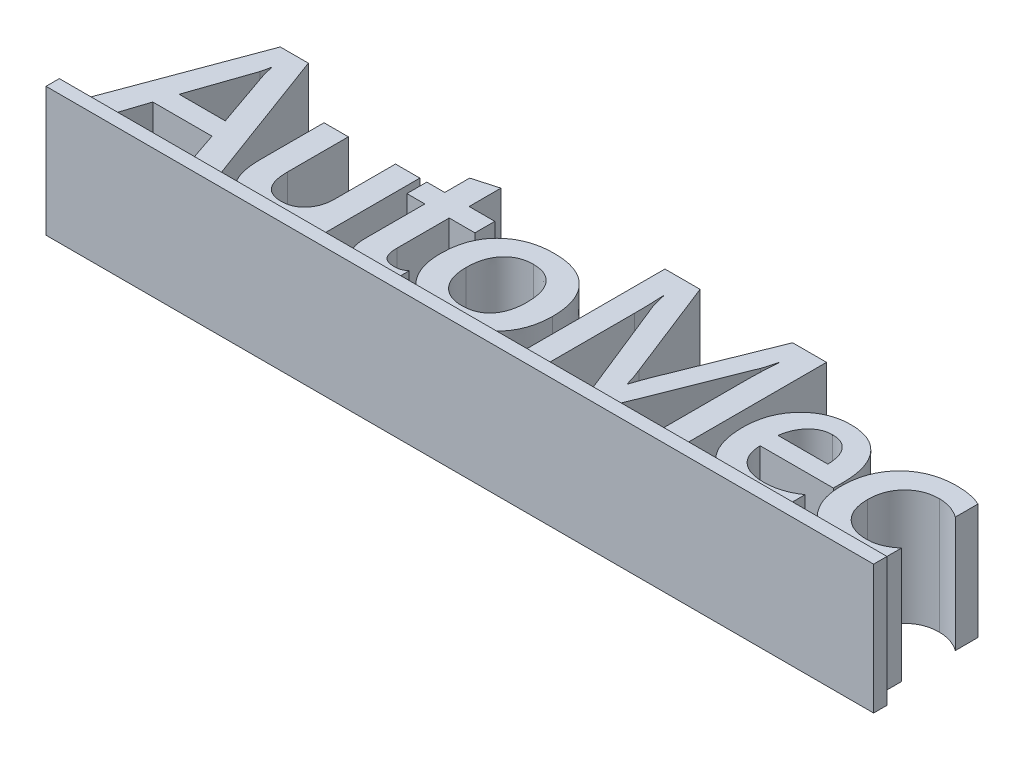
SolidWorks part; units mm, degrees
ref_plane "Front Plane" through (0, 0, 0) normal (0, 0, 1) x (1, 0, 0)
ref_plane "Top Plane" through (0, 0, 0) normal (0, 1, 0) x (1, 0, 0)
ref_plane "Right Plane" through (0, 0, 0) normal (1, 0, 0) x (0, 0, -1)
sketch "Sketch3" plane through (0, 0, 0) normal (0, 1, 0) x (1, 0, 0)
  text T0 "AutoMec" font "@Yu Gothic UI" height 34
  point P1 (0, 0)
  point P2 (0, 0)
  point P3 (0, 0)
  dimension "D1" = 2
extrude "Boss-Extrude3" add sketch "Sketch3" along normal blind 26
sketch "Sketch8" plane through (0, 0, 0) normal (0, 1, 0) x (1, 0, 0)
  line L0 (182.4796, 6.2632) -> (182.4796, 1.3002) construction
  line L1 (-0.6016, 0) -> (185.4796, 0)
  line L2 (-0.6016, 0) -> (-0.6016, -3)
  line L3 (-0.6016, -3) -> (185.4796, -3)
  line L4 (185.4796, 0) -> (185.4796, -3)
  line L5 (8.5358, 0) -> (2.3984, 0) construction
  point P8 (0, 0)
  dimension "D1" = 3
  dimension "D2" = 3
  dimension "D3" = 3
extrude "Boss-Extrude6" add sketch "Sketch8" along normal blind 29
sketch "Sketch9" plane through (0, 0, 0) normal (0, 1, 0) x (1, 0, 0)
  line L0 (185.4796, 0) -> (-0.6016, 0) construction
  line L1 (50.8205, 4.0752) -> (46.2162, 4.0752)
  line L2 (50.8205, 4.0752) -> (50.8205, 0)
  line L3 (50.8205, 0) -> (46.2162, 0)
  line L4 (46.2162, 4.0752) -> (46.2162, 0)
  spline S0 degree 3 poles (50.7226, 4.0752) (50.5199, 3.7151) (50.1266, 3.0161) (49.3956, 2.0918) (48.5875, 1.308) (47.6958, 0.6594) (46.8879, 0.2502) (46.3829, 0.0573) (46.2162, 0) knots 0 0 0 0 0.134966 0.261921 0.383686 0.502095 0.621005 0.678615 0.678615 0.678615 0.678615 construction
extrude "Boss-Extrude7" add sketch "Sketch9" along normal up to surface (26 mm away) up to face at (85.7722, 26, -12.0388)
sketch "Sketch10" plane through (0, 0, 0) normal (0, 1, 0) x (1, 0, 0)
  line L1 (73.1484, 0.3914) -> (72.2012, 0.3914)
  line L2 (73.1484, 0.3914) -> (73.1484, 0)
  line L3 (73.1484, 0) -> (72.2012, 0)
  line L4 (72.2012, 0.3914) -> (72.2012, 0)
extrude "Boss-Extrude8" add sketch "Sketch10" along normal up to surface (26 mm away) up to face at (66.6817, 26, -15.2052)
sketch "Sketch11" plane through (0, 0, 0) normal (0, 1, 0) x (1, 0, 0)
  line L1 (161.2492, 1.5588) -> (157.1624, 1.5588)
  line L2 (161.2492, 1.5588) -> (161.2492, 0)
  line L3 (161.2492, 0) -> (157.1624, 0)
  line L4 (157.1624, 1.5588) -> (157.1624, 0)
extrude "Boss-Extrude9" add sketch "Sketch11" along normal up to surface (26 mm away) up to face at (154.266, 26, -16.4035)
sketch "Sketch12" plane through (0, 0, 0) normal (0, 1, 0) x (1, 0, 0)
  line L1 (182.4796, 1.3002) -> (179.3332, 1.3002)
  line L2 (182.4796, 1.3002) -> (182.4796, 0)
  line L3 (182.4796, 0) -> (179.3332, 0)
  line L4 (179.3332, 1.3002) -> (179.3332, 0)
extrude "Boss-Extrude10" add sketch "Sketch12" along normal up to surface (26 mm away) up to face at (176.4629, 26, -10.5894)
